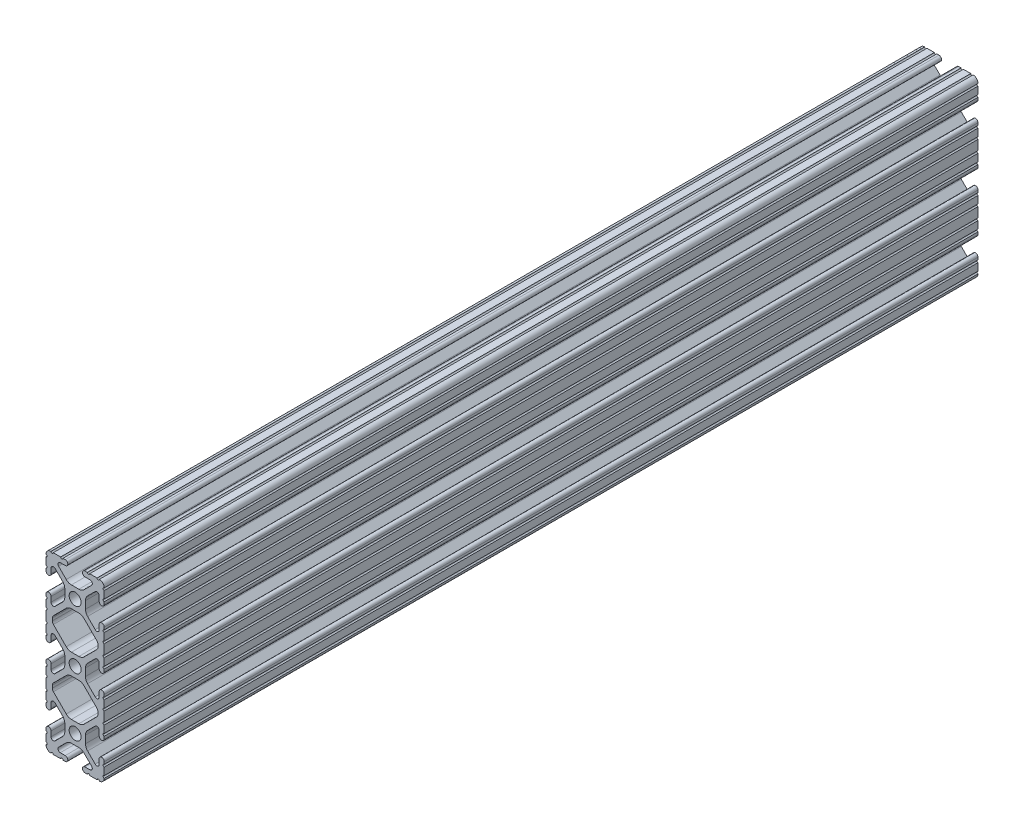
SolidWorks part; units mm, degrees
ref_plane "Front" through (0, 0, 0) normal (0, 0, 1) x (1, 0, 0)
ref_plane "Top" through (0, 0, 0) normal (0, 1, 0) x (1, 0, 0)
ref_plane "Right" through (0, 0, 0) normal (1, 0, 0) x (0, 0, -1)
sketch "Sketch1" plane through (0, 0, 0) normal (0, 0, 1) x (1, 0, 0)
  line L0 (-7.4908, -34.8742) -> (7.4908, -34.8742) construction
  line L1 (-3.1974, -36.9951) -> (3.1974, -36.9951) construction
  line L2 (-7.4908, 34.8742) -> (7.4908, 34.8742) construction
  line L3 (-3.1974, 36.9951) -> (3.1974, 36.9951) construction
  line L16 (-9.9314, -12.1463) -> (-9.9314, -13.2537)
  line L17 (-3.8759, -5.4384) -> (-9.4702, -11.0327)
  line L18 (1.6308, -4.5085) -> (-1.6308, -4.5085)
  line L19 (9.4702, -11.0327) -> (3.8759, -5.4384)
  line L20 (9.9314, -13.2537) -> (9.9314, -12.1463)
  line L21 (3.8759, -19.9616) -> (9.4702, -14.3673)
  line L22 (-1.6308, -20.8915) -> (1.6308, -20.8915)
  line L23 (-9.4702, -14.3673) -> (-3.8759, -19.9616)
  line L32 (-9.9314, 13.2537) -> (-9.9314, 12.1463)
  line L33 (-3.8759, 19.9616) -> (-9.4702, 14.3673)
  line L34 (1.6308, 20.8915) -> (-1.6308, 20.8915)
  line L35 (9.4702, 14.3673) -> (3.8759, 19.9616)
  line L36 (9.9314, 12.1463) -> (9.9314, 13.2537)
  line L37 (3.8759, 5.4384) -> (9.4702, 11.0327)
  line L38 (-1.6308, 4.5085) -> (1.6308, 4.5085)
  line L39 (-9.4702, 11.0327) -> (-3.8759, 5.4384)
  line L152 (-12.7, 34.9504) -> (-12.7, 31.7246)
  line L153 (-12.7, 30.7086) -> (-12.7, 29.7023)
  line L154 (-10.4902, 29.7023) -> (-10.4902, 31.8748)
  line L155 (-8.7558, 32.5932) -> (-5.4384, 29.2759)
  line L156 (-4.5085, 27.0308) -> (-4.5085, 23.7692)
  line L157 (-5.4384, 21.5241) -> (-8.7558, 18.2068)
  line L158 (-10.4902, 18.9252) -> (-10.4902, 21.0977)
  line L159 (-12.7, 21.0977) -> (-12.7, 20.0914)
  line L160 (-12.7, 19.0754) -> (-12.7, 15.8496)
  line L161 (-12.7, 14.8336) -> (-12.7, 10.5664)
  line L162 (-12.7, 9.5504) -> (-12.7, 6.3246)
  line L163 (-12.7, 5.3086) -> (-12.7, 4.3023)
  line L164 (-10.4902, 4.3023) -> (-10.4902, 6.4748)
  line L165 (-8.7558, 7.1932) -> (-5.4384, 3.8759)
  line L166 (-4.5085, 1.6308) -> (-4.5085, -1.6308)
  line L167 (-5.4384, -3.8759) -> (-8.7558, -7.1932)
  line L168 (-10.4902, -6.4748) -> (-10.4902, -4.3023)
  line L169 (-12.7, -4.3023) -> (-12.7, -5.3086)
  line L170 (-12.7, -6.3246) -> (-12.7, -9.5504)
  line L171 (-12.7, -10.5664) -> (-12.7, -14.8336)
  line L172 (-12.7, -15.8496) -> (-12.7, -19.0754)
  line L173 (-12.7, -20.0914) -> (-12.7, -21.0977)
  line L174 (-10.4902, -21.0977) -> (-10.4902, -18.9252)
  line L175 (-8.7558, -18.2068) -> (-5.4384, -21.5241)
  line L176 (-4.5085, -23.7692) -> (-4.5085, -27.0308)
  line L177 (-5.4384, -29.2759) -> (-8.7558, -32.5932)
  line L178 (-10.4902, -31.8748) -> (-10.4902, -29.7023)
  line L179 (-12.7, -29.7023) -> (-12.7, -30.7086)
  line L180 (-12.7, -31.7246) -> (-12.7, -34.9504)
  line L181 (-9.5504, -38.1) -> (-6.3246, -38.1)
  line L182 (-5.3086, -38.1) -> (-4.3023, -38.1)
  line L183 (-4.3023, -35.8902) -> (-6.4748, -35.8902)
  line L184 (-7.1932, -34.1558) -> (-3.8759, -30.8384)
  line L185 (-1.6308, -29.9085) -> (1.6308, -29.9085)
  line L186 (3.8759, -30.8384) -> (7.1932, -34.1558)
  line L187 (6.4748, -35.8902) -> (4.3023, -35.8902)
  line L188 (4.3023, -38.1) -> (5.3086, -38.1)
  line L189 (6.3246, -38.1) -> (9.5504, -38.1)
  line L190 (12.7, -34.9504) -> (12.7, -31.7246)
  line L191 (12.7, -30.7086) -> (12.7, -29.7023)
  line L192 (10.4902, -29.7023) -> (10.4902, -31.8748)
  line L193 (8.7558, -32.5932) -> (5.4384, -29.2759)
  line L194 (4.5085, -27.0308) -> (4.5085, -23.7692)
  line L195 (5.4384, -21.5241) -> (8.7558, -18.2068)
  line L196 (10.4902, -18.9252) -> (10.4902, -21.0977)
  line L197 (12.7, -21.0977) -> (12.7, -20.0914)
  line L198 (12.7, -19.0754) -> (12.7, -15.8496)
  line L199 (12.7, -14.8336) -> (12.7, -10.5664)
  line L200 (12.7, -9.5504) -> (12.7, -6.3246)
  line L201 (12.7, -5.3086) -> (12.7, -4.3023)
  line L202 (10.4902, -4.3023) -> (10.4902, -6.4748)
  line L203 (8.7558, -7.1932) -> (5.4384, -3.8759)
  line L204 (4.5085, -1.6308) -> (4.5085, 1.6308)
  line L205 (5.4384, 3.8759) -> (8.7558, 7.1932)
  line L206 (10.4902, 6.4748) -> (10.4902, 4.3023)
  line L207 (12.7, 4.3023) -> (12.7, 5.3086)
  line L208 (12.7, 6.3246) -> (12.7, 9.5504)
  line L209 (12.7, 10.5664) -> (12.7, 14.8336)
  line L210 (12.7, 15.8496) -> (12.7, 19.0754)
  line L211 (12.7, 20.0914) -> (12.7, 21.0977)
  line L212 (10.4902, 21.0977) -> (10.4902, 18.9252)
  line L213 (8.7558, 18.2068) -> (5.4384, 21.5241)
  line L214 (4.5085, 23.7692) -> (4.5085, 27.0308)
  line L215 (5.4384, 29.2759) -> (8.7558, 32.5932)
  line L216 (10.4902, 31.8748) -> (10.4902, 29.7023)
  line L217 (12.7, 29.7023) -> (12.7, 30.7086)
  line L218 (12.7, 31.7246) -> (12.7, 34.9504)
  line L219 (9.5504, 38.1) -> (6.3246, 38.1)
  line L220 (5.3086, 38.1) -> (4.3023, 38.1)
  line L221 (4.3023, 35.8902) -> (6.4748, 35.8902)
  line L222 (7.1932, 34.1558) -> (3.8759, 30.8384)
  line L223 (1.6308, 29.9085) -> (-1.6308, 29.9085)
  line L224 (-3.8759, 30.8384) -> (-7.1932, 34.1558)
  line L225 (-6.4748, 35.8902) -> (-4.3023, 35.8902)
  line L226 (-4.3023, 38.1) -> (-5.3086, 38.1)
  line L227 (-6.3246, 38.1) -> (-9.5504, 38.1)
  circle A2 centre (0, -25.4) radius 2.6035
  circle A4 centre (0, 0) radius 2.6035
  circle A6 centre (0, 25.4) radius 2.6035
  arc A18 (-9.9314, -13.2537) -> (-9.4702, -14.3673) centre (-8.3566, -13.2537) ccw
  arc A19 (-9.4702, -11.0327) -> (-9.9314, -12.1463) centre (-8.3566, -12.1463) ccw
  arc A20 (-1.6308, -4.5085) -> (-3.8759, -5.4384) centre (-1.6308, -7.6835) ccw
  arc A21 (3.8759, -5.4384) -> (1.6308, -4.5085) centre (1.6308, -7.6835) ccw
  arc A22 (9.9314, -12.1463) -> (9.4702, -11.0327) centre (8.3566, -12.1463) ccw
  arc A23 (9.4702, -14.3673) -> (9.9314, -13.2537) centre (8.3566, -13.2537) ccw
  arc A24 (1.6308, -20.8915) -> (3.8759, -19.9616) centre (1.6308, -17.7165) ccw
  arc A25 (-3.8759, -19.9616) -> (-1.6308, -20.8915) centre (-1.6308, -17.7165) ccw
  arc A36 (-9.9314, 12.1463) -> (-9.4702, 11.0327) centre (-8.3566, 12.1463) ccw
  arc A37 (-9.4702, 14.3673) -> (-9.9314, 13.2537) centre (-8.3566, 13.2537) ccw
  arc A38 (-1.6308, 20.8915) -> (-3.8759, 19.9616) centre (-1.6308, 17.7165) ccw
  arc A39 (3.8759, 19.9616) -> (1.6308, 20.8915) centre (1.6308, 17.7165) ccw
  arc A40 (9.9314, 13.2537) -> (9.4702, 14.3673) centre (8.3566, 13.2537) ccw
  arc A41 (9.4702, 11.0327) -> (9.9314, 12.1463) centre (8.3566, 12.1463) ccw
  arc A42 (1.6308, 4.5085) -> (3.8759, 5.4384) centre (1.6308, 7.6835) ccw
  arc A43 (-3.8759, 5.4384) -> (-1.6308, 4.5085) centre (-1.6308, 7.6835) ccw
  arc A168 (-10.5664, 38.1) -> (-12.7, 35.9664) centre (-10.592, 35.992) ccw
  arc A169 (-12.7, 34.9504) -> (-12.7, 35.9664) centre (-12.7, 35.4584) ccw
  arc A170 (-12.7, 30.7086) -> (-12.7, 31.7246) centre (-12.7, 31.2166) ccw
  arc A171 (-12.7, 29.7023) -> (-10.4902, 29.7023) centre (-11.5951, 29.7023) ccw
  arc A172 (-8.7558, 32.5932) -> (-10.4902, 31.8748) centre (-9.4742, 31.8748) ccw
  arc A173 (-4.5085, 27.0308) -> (-5.4384, 29.2759) centre (-7.6835, 27.0308) ccw
  arc A174 (-5.4384, 21.5241) -> (-4.5085, 23.7692) centre (-7.6835, 23.7692) ccw
  arc A175 (-10.4902, 18.9252) -> (-8.7558, 18.2068) centre (-9.4742, 18.9252) ccw
  arc A176 (-10.4902, 21.0977) -> (-12.7, 21.0977) centre (-11.5951, 21.0977) ccw
  arc A177 (-12.7, 19.0754) -> (-12.7, 20.0914) centre (-12.7, 19.5834) ccw
  arc A178 (-12.7, 14.8336) -> (-12.7, 15.8496) centre (-12.7, 15.3416) ccw
  arc A179 (-12.7, 9.5504) -> (-12.7, 10.5664) centre (-12.7, 10.0584) ccw
  arc A180 (-12.7, 5.3086) -> (-12.7, 6.3246) centre (-12.7, 5.8166) ccw
  arc A181 (-12.7, 4.3023) -> (-10.4902, 4.3023) centre (-11.5951, 4.3023) ccw
  arc A182 (-8.7558, 7.1932) -> (-10.4902, 6.4748) centre (-9.4742, 6.4748) ccw
  arc A183 (-4.5085, 1.6308) -> (-5.4384, 3.8759) centre (-7.6835, 1.6308) ccw
  arc A184 (-5.4384, -3.8759) -> (-4.5085, -1.6308) centre (-7.6835, -1.6308) ccw
  arc A185 (-10.4902, -6.4748) -> (-8.7558, -7.1932) centre (-9.4742, -6.4748) ccw
  arc A186 (-10.4902, -4.3023) -> (-12.7, -4.3023) centre (-11.5951, -4.3023) ccw
  arc A187 (-12.7, -6.3246) -> (-12.7, -5.3086) centre (-12.7, -5.8166) ccw
  arc A188 (-12.7, -10.5664) -> (-12.7, -9.5504) centre (-12.7, -10.0584) ccw
  arc A189 (-12.7, -15.8496) -> (-12.7, -14.8336) centre (-12.7, -15.3416) ccw
  arc A190 (-12.7, -20.0914) -> (-12.7, -19.0754) centre (-12.7, -19.5834) ccw
  arc A191 (-12.7, -21.0977) -> (-10.4902, -21.0977) centre (-11.5951, -21.0977) ccw
  arc A192 (-8.7558, -18.2068) -> (-10.4902, -18.9252) centre (-9.4742, -18.9252) ccw
  arc A193 (-4.5085, -23.7692) -> (-5.4384, -21.5241) centre (-7.6835, -23.7692) ccw
  arc A194 (-5.4384, -29.2759) -> (-4.5085, -27.0308) centre (-7.6835, -27.0308) ccw
  arc A195 (-10.4902, -31.8748) -> (-8.7558, -32.5932) centre (-9.4742, -31.8748) ccw
  arc A196 (-10.4902, -29.7023) -> (-12.7, -29.7023) centre (-11.5951, -29.7023) ccw
  arc A197 (-12.7, -31.7246) -> (-12.7, -30.7086) centre (-12.7, -31.2166) ccw
  arc A198 (-12.7, -35.9664) -> (-12.7, -34.9504) centre (-12.7, -35.4584) ccw
  arc A199 (-12.7, -35.9664) -> (-10.5664, -38.1) centre (-10.592, -35.992) ccw
  arc A200 (-9.5504, -38.1) -> (-10.5664, -38.1) centre (-10.0584, -38.1) ccw
  arc A201 (-5.3086, -38.1) -> (-6.3246, -38.1) centre (-5.8166, -38.1) ccw
  arc A202 (-4.3023, -38.1) -> (-4.3023, -35.8902) centre (-4.3023, -36.9951) ccw
  arc A203 (-7.1932, -34.1558) -> (-6.4748, -35.8902) centre (-6.4748, -34.8742) ccw
  arc A204 (-1.6308, -29.9085) -> (-3.8759, -30.8384) centre (-1.6308, -33.0835) ccw
  arc A205 (3.8759, -30.8384) -> (1.6308, -29.9085) centre (1.6308, -33.0835) ccw
  arc A206 (6.4748, -35.8902) -> (7.1932, -34.1558) centre (6.4748, -34.8742) ccw
  arc A207 (4.3023, -35.8902) -> (4.3023, -38.1) centre (4.3023, -36.9951) ccw
  arc A208 (6.3246, -38.1) -> (5.3086, -38.1) centre (5.8166, -38.1) ccw
  arc A209 (10.5664, -38.1) -> (9.5504, -38.1) centre (10.0584, -38.1) ccw
  arc A210 (10.5664, -38.1) -> (12.7, -35.9664) centre (10.592, -35.992) ccw
  arc A211 (12.7, -34.9504) -> (12.7, -35.9664) centre (12.7, -35.4584) ccw
  arc A212 (12.7, -30.7086) -> (12.7, -31.7246) centre (12.7, -31.2166) ccw
  arc A213 (12.7, -29.7023) -> (10.4902, -29.7023) centre (11.5951, -29.7023) ccw
  arc A214 (8.7558, -32.5932) -> (10.4902, -31.8748) centre (9.4742, -31.8748) ccw
  arc A215 (4.5085, -27.0308) -> (5.4384, -29.2759) centre (7.6835, -27.0308) ccw
  arc A216 (5.4384, -21.5241) -> (4.5085, -23.7692) centre (7.6835, -23.7692) ccw
  arc A217 (10.4902, -18.9252) -> (8.7558, -18.2068) centre (9.4742, -18.9252) ccw
  arc A218 (10.4902, -21.0977) -> (12.7, -21.0977) centre (11.5951, -21.0977) ccw
  arc A219 (12.7, -19.0754) -> (12.7, -20.0914) centre (12.7, -19.5834) ccw
  arc A220 (12.7, -14.8336) -> (12.7, -15.8496) centre (12.7, -15.3416) ccw
  arc A221 (12.7, -9.5504) -> (12.7, -10.5664) centre (12.7, -10.0584) ccw
  arc A222 (12.7, -5.3086) -> (12.7, -6.3246) centre (12.7, -5.8166) ccw
  arc A223 (12.7, -4.3023) -> (10.4902, -4.3023) centre (11.5951, -4.3023) ccw
  arc A224 (8.7558, -7.1932) -> (10.4902, -6.4748) centre (9.4742, -6.4748) ccw
  arc A225 (4.5085, -1.6308) -> (5.4384, -3.8759) centre (7.6835, -1.6308) ccw
  arc A226 (5.4384, 3.8759) -> (4.5085, 1.6308) centre (7.6835, 1.6308) ccw
  arc A227 (10.4902, 6.4748) -> (8.7558, 7.1932) centre (9.4742, 6.4748) ccw
  arc A228 (10.4902, 4.3023) -> (12.7, 4.3023) centre (11.5951, 4.3023) ccw
  arc A229 (12.7, 6.3246) -> (12.7, 5.3086) centre (12.7, 5.8166) ccw
  arc A230 (12.7, 10.5664) -> (12.7, 9.5504) centre (12.7, 10.0584) ccw
  arc A231 (12.7, 15.8496) -> (12.7, 14.8336) centre (12.7, 15.3416) ccw
  arc A232 (12.7, 20.0914) -> (12.7, 19.0754) centre (12.7, 19.5834) ccw
  arc A233 (12.7, 21.0977) -> (10.4902, 21.0977) centre (11.5951, 21.0977) ccw
  arc A234 (8.7558, 18.2068) -> (10.4902, 18.9252) centre (9.4742, 18.9252) ccw
  arc A235 (4.5085, 23.7692) -> (5.4384, 21.5241) centre (7.6835, 23.7692) ccw
  arc A236 (5.4384, 29.2759) -> (4.5085, 27.0308) centre (7.6835, 27.0308) ccw
  arc A237 (10.4902, 31.8748) -> (8.7558, 32.5932) centre (9.4742, 31.8748) ccw
  arc A238 (10.4902, 29.7023) -> (12.7, 29.7023) centre (11.5951, 29.7023) ccw
  arc A239 (12.7, 31.7246) -> (12.7, 30.7086) centre (12.7, 31.2166) ccw
  arc A240 (12.7, 35.9664) -> (12.7, 34.9504) centre (12.7, 35.4584) ccw
  arc A241 (12.7, 35.9664) -> (10.5664, 38.1) centre (10.592, 35.992) ccw
  arc A242 (9.5504, 38.1) -> (10.5664, 38.1) centre (10.0584, 38.1) ccw
  arc A243 (5.3086, 38.1) -> (6.3246, 38.1) centre (5.8166, 38.1) ccw
  arc A244 (4.3023, 38.1) -> (4.3023, 35.8902) centre (4.3023, 36.9951) ccw
  arc A245 (7.1932, 34.1558) -> (6.4748, 35.8902) centre (6.4748, 34.8742) ccw
  arc A246 (1.6308, 29.9085) -> (3.8759, 30.8384) centre (1.6308, 33.0835) ccw
  arc A247 (-3.8759, 30.8384) -> (-1.6308, 29.9085) centre (-1.6308, 33.0835) ccw
  arc A248 (-6.4748, 35.8902) -> (-7.1932, 34.1558) centre (-6.4748, 34.8742) ccw
  arc A249 (-4.3023, 35.8902) -> (-4.3023, 38.1) centre (-4.3023, 36.9951) ccw
  arc A250 (-6.3246, 38.1) -> (-5.3086, 38.1) centre (-5.8166, 38.1) ccw
  arc A251 (-10.5664, 38.1) -> (-9.5504, 38.1) centre (-10.0584, 38.1) ccw
extrude "Boss-Extrude1" add sketch "Sketch1" along normal mid plane 381
